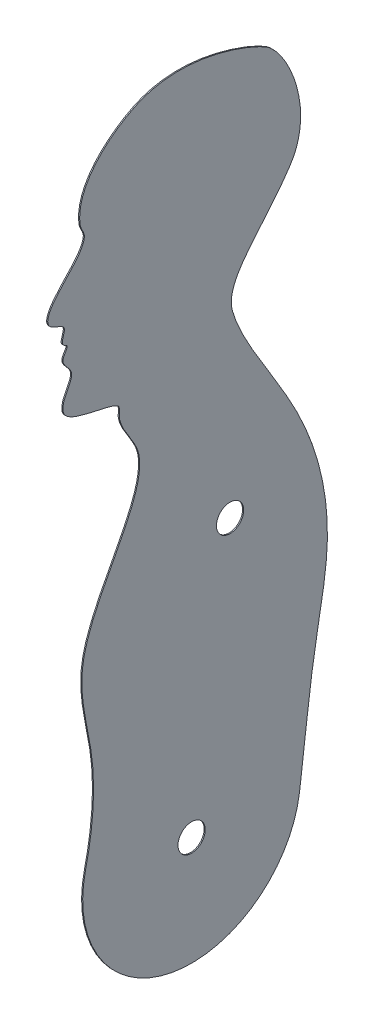
SolidWorks part; units mm, degrees
material "Teras S325"
ref_plane "Front Plane" through (0, 0, 0) normal (0, 0, 1) x (1, 0, 0)
ref_plane "Top Plane" through (0, 0, 0) normal (0, 1, 0) x (1, 0, 0)
ref_plane "Right Plane" through (0, 0, 0) normal (1, 0, 0) x (0, 0, -1)
sketch "Sketch3" plane through (0, 0, 0) normal (1, 0, 0) x (0, 0, -1)
  line L0 (35.2923, 236.4157) -> (0, 0) construction
  arc A0 (-97.4177, 22.5787) -> (99.0996, -13.3893) centre (0, 0) ccw
  circle A1 centre (0, 0) radius 12.5
  circle A2 centre (35.2923, 236.4157) radius 12.5
  spline S0 degree 3 poles (69.2754, 593.6762) (57.6118, 601.5201) (-6.5419, 629.5132) (-78.7941, 593.7489) (-106.0816, 568.2411) (-101.8908, 534.2082) (-98.1302, 530.4079) (-99.612, 512.1853) (-126.9605, 494.4916) (-135.4097, 466.7349) (-108.1707, 470.4356) (-121.9781, 451.1064) (-111.4876, 447.8679) (-123.3435, 436.943) (-100.3228, 422.7218) (-119.8579, 409.2611) (-115.7101, 384.0976) (-75.3452, 383.2995) (-65.0484, 374.5779) (-66.9834, 369.6309) (-63.4028, 352.7922) (-52.228, 342.6397) (-38.6626, 293.3422) (-118.8057, 209.8772) (-86.5504, 110.2371) (-89.6912, 55.9152) (-97.4177, 22.5787) knots 0 0 0 0 0.136132 0.136132 0.213378 0.213378 0.225241 0.225241 0.268362 0.268362 0.305383 0.326231 0.332003 0.347547 0.372102 0.421707 0.421707 0.477771 0.477771 0.495457 0.495457 0.55979 0.55979 0.766583 0.871741 1 1 1 1
  spline S1 degree 3 poles (99.0996, -13.3893) (104.0177, 23.0114) (109.6309, 83.611) (132.4162, 185.9531) (106.6179, 291.4366) (45.8135, 369.4) (30.04, 427.0265) (66.5329, 452.4808) (113.5867, 524.6326) (89.5891, 580.0151) (69.2754, 593.6762) knots 0 0 0 0 0.172373 0.285417 0.484157 0.676147 0.676147 0.843592 0.843592 1 1 1 1
  dimension "D1" = 200
  dimension "D2" = 25
  dimension "D3" = 25
extrude "Extrude1" add sketch "Sketch3" along normal mid plane 1
